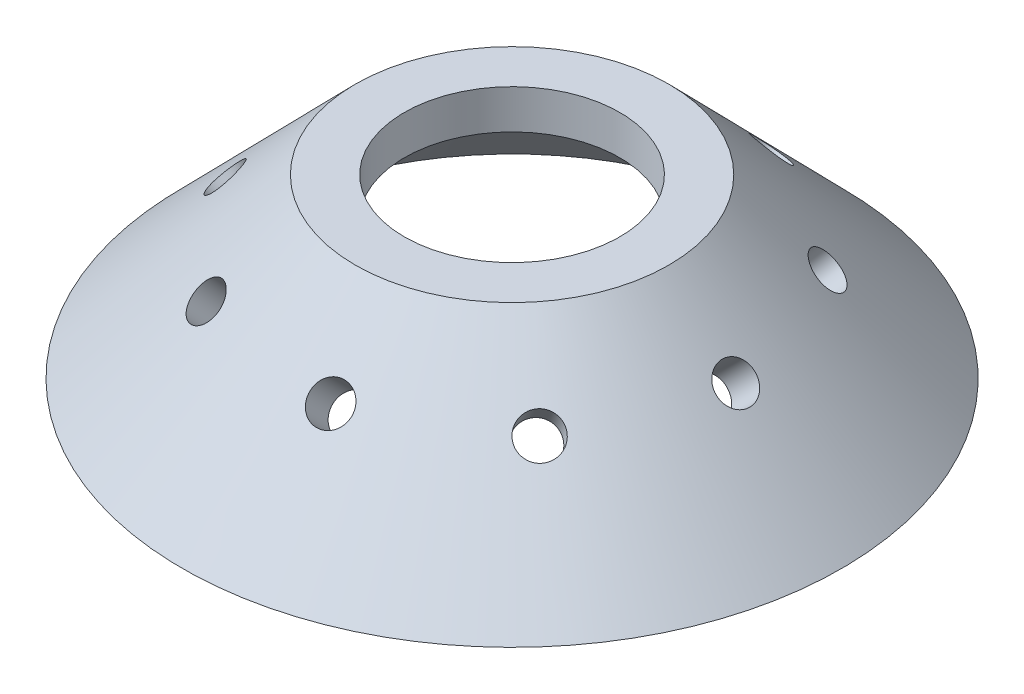
SolidWorks part; units mm, degrees
ref_plane "Front Plane" through (0, 0, 0) normal (0, 0, 1) x (1, 0, 0)
ref_plane "Top Plane" through (0, 0, 0) normal (0, 1, 0) x (1, 0, 0)
ref_plane "Right Plane" through (0, 0, 0) normal (1, 0, 0) x (0, 0, -1)
sketch "Sketch6" plane through (0, 0, 0) normal (0, 0, 1) x (1, 0, 0)
  line L2 (42.0454, -22.5) -> (20, 0)
  line L3 (20, 0) -> (0, 0)
  line L4 (42.0454, -22.5) -> (35.0454, -22.5)
  line L5 (35.0454, -22.5) -> (17.899, -5)
  line L6 (17.899, -5) -> (0, -5)
  line L7 (0, -5) -> (0, 0)
  line L8 (0, -5) -> (0, -22.5) construction
  line L9 (0, -22.5) -> (35.0454, -22.5) construction
  line L10 (42.0454, -22.5) -> (42.0454, -8.75) construction
  line L11 (42.0454, -8.75) -> (28.5732, -8.75) construction
  dimension "D2" = 5
  dimension "D3" = 20
  dimension "D1" = 5
  dimension "D4" = 7
  dimension "D5" = 22.5
  dimension "D6" = 13.75
revolve "Revolve2" add sketch "Sketch6" angle 360 about L7
ref_plane "Plane1" through (10.2041, 9.9979, 0) normal (0.7143, 0.6999, 0) x (0, 0, -1)
sketch "Sketch11" plane through (0, 0, 0) normal (0, 1, 0) x (1, 0, 0)
  line L0 (-20, 0) -> (20, 0) construction
  circle A0 centre (0, 0) radius 13.75
  circle A2 centre (0, 0) radius 20 construction
  dimension "D1" = 27.5
extrude "Cut-Extrude1" cut sketch "Sketch11" against normal through all
sketch "Sketch24" plane through (10.2041, 9.9979, 0) normal (0.7143, 0.6999, 0) x (0, 0, -1)
  circle A0 centre (0, -26.2471) radius 2.5
  dimension "D1" = 5
extrude "Cut-Extrude2" cut sketch "Sketch24" against normal through all contours A0
pattern_circular "CirPattern10" count 9 over 360 about axis through (0, -5, 0) along (0, -1, 0) of "Cut-Extrude2"
equation "\"height\"= 3cm"
equation "\"D5@Sketch6\"=\"height\" * 0.75"
equation "\"D6@Sketch6\"=\"height\" * 0.75/2 + 0.25"
